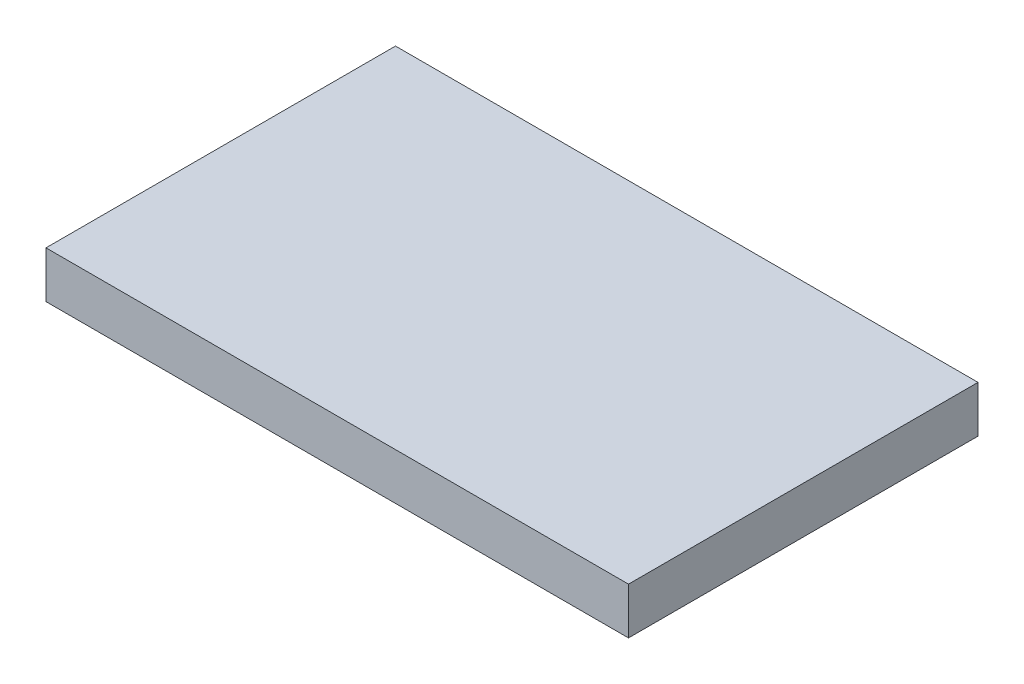
SolidWorks part; units mm, degrees
material "Медь"
ref_plane "Спереди" through (0, 0, 0) normal (0, 0, 1) x (1, 0, 0)
ref_plane "Сверху" through (0, 0, 0) normal (0, 1, 0) x (1, 0, 0)
ref_plane "Справа" through (0, 0, 0) normal (1, 0, 0) x (0, 0, -1)
sketch "Эскиз1" plane through (0, 0, 0) normal (0, 1, 0) x (1, 0, 0)
  line L1 (-12.5, 7.5) -> (12.5, 7.5)
  line L2 (-12.5, 7.5) -> (-12.5, -7.5)
  line L3 (-12.5, -7.5) -> (12.5, -7.5)
  line L4 (12.5, 7.5) -> (12.5, -7.5)
  line L5 (-12.5, 7.5) -> (12.5, -7.5) construction
  line L6 (-12.5, -7.5) -> (12.5, 7.5) construction
  point P0 (0, 0)
  dimension "D1" = 25
  dimension "D2" = 15
extrude "Бобышка-Вытянуть1" add sketch "Эскиз1" along normal blind 2
